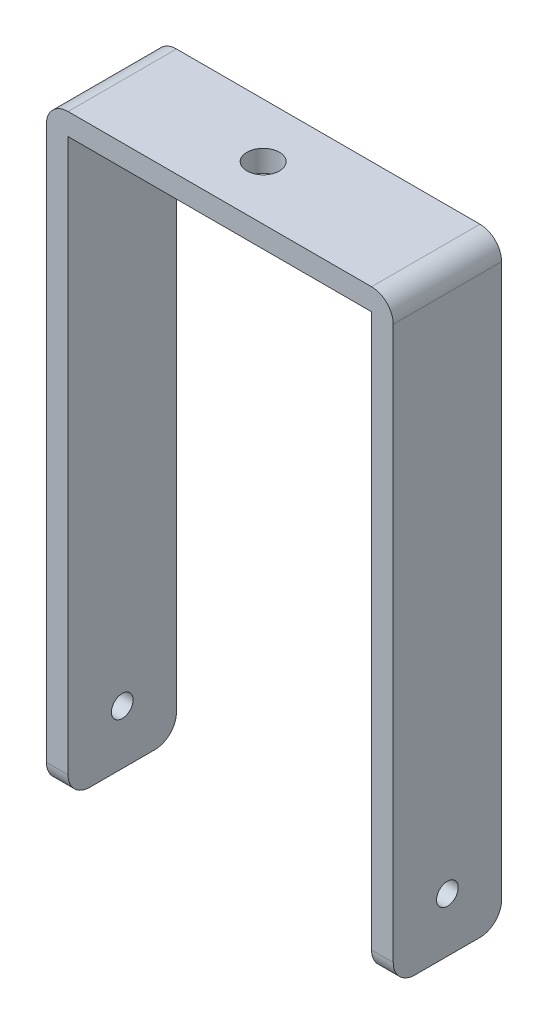
SolidWorks part; units mm, degrees
ref_plane "Front Plane" through (0, 0, 0) normal (0, 0, 1) x (1, 0, 0)
ref_plane "Top Plane" through (0, 0, 0) normal (0, 1, 0) x (1, 0, 0)
ref_plane "Right Plane" through (0, 0, 0) normal (1, 0, 0) x (0, 0, -1)
sketch "Sketch1" plane through (0, 0, 0) normal (0, 0, 1) x (1, 0, 0)
  line L0 (0, 0) -> (0, 275)
  line L1 (0, 275) -> (160, 275)
  line L2 (160, 275) -> (160, 0)
  line L3 (160, 0) -> (150, 0)
  line L4 (150, 0) -> (150, 265)
  line L5 (150, 265) -> (10, 265)
  line L6 (10, 265) -> (10, 0)
  line L7 (10, 0) -> (0, 0)
  dimension "D1" = 160
  dimension "D2" = 10
  dimension "D3" = 10
  dimension "D4" = 10
  dimension "D5" = 275
extrude "Boss-Extrude1" add sketch "Sketch1" along normal blind 50
fillet "Fillet1" radius 10 6 edges at (0, 275, 25) (160, 275, 25) (5, 0, 50) (5, 0, 0) (155, 0, 50) (155, 0, 0)
sketch "Sketch2" plane through (0, 0, 0) normal (-1, 0, 0) x (0, 0, 1)
  line L0 (0, 265) -> (0, 10) construction
  line L1 (40, 0) -> (10, 0) construction
  circle A0 centre (25, 25) radius 5
  point P4 (0, 0)
  point P6 (36.1499, 4.0645)
  dimension "D1" = 10
  dimension "D2" = 25
  dimension "D3" = 25
extrude "Cut-Extrude1" cut sketch "Sketch2" against normal blind 170
sketch "Sketch4" plane through (0, 275, 0) normal (0, 1, 0) x (1, 0, 0)
  line L0 (150, -50) -> (150, 0) construction
  line L1 (150, -50) -> (10, -50) construction
  circle A0 centre (75, -25) radius 7.5
  point P4 (0, 0)
  point P6 (84.5967, -29.9999)
  dimension "D1" = 15
  dimension "D2" = 75
  dimension "D3" = 25
extrude "Cut-Extrude2" cut sketch "Sketch4" against normal blind 10
